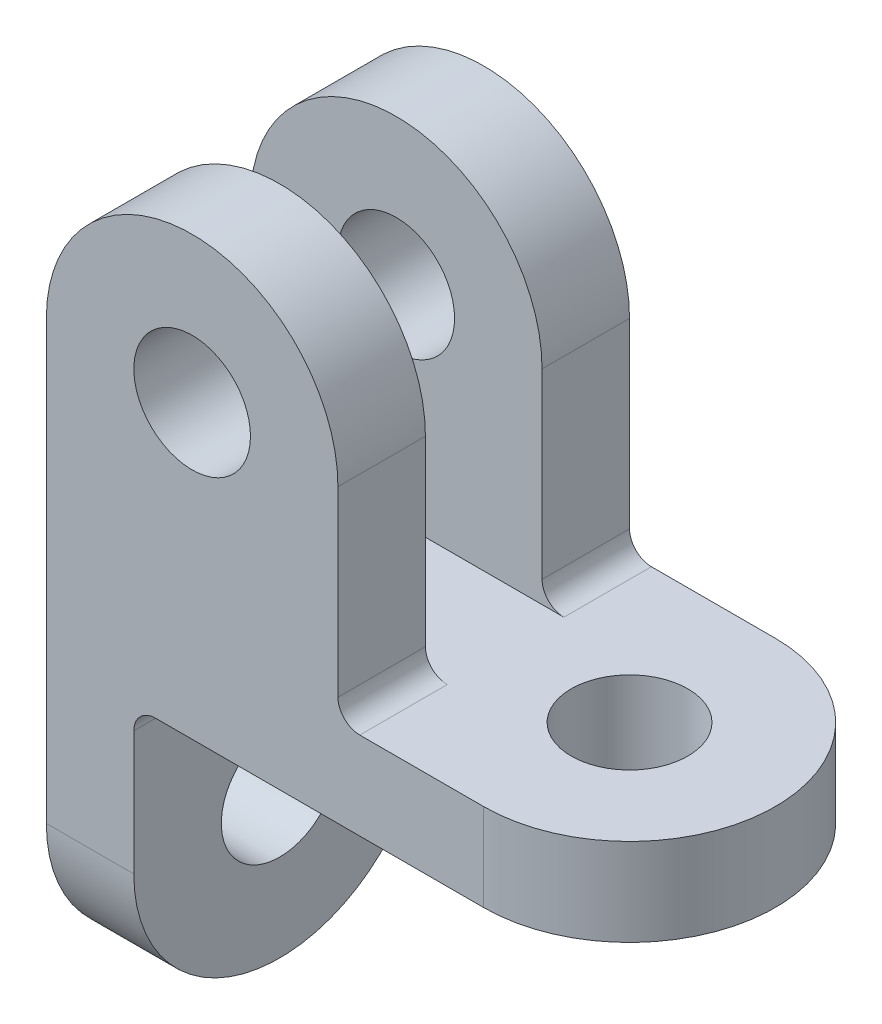
SolidWorks part; units mm, degrees
ref_plane "Front Plane" through (0, 0, 0) normal (0, 0, 1) x (1, 0, 0)
ref_plane "Top Plane" through (0, 0, 0) normal (0, 1, 0) x (1, 0, 0)
ref_plane "Right Plane" through (0, 0, 0) normal (1, 0, 0) x (0, 0, -1)
sketch "Sketch1" plane through (0, 0, 0) normal (0, 0, 1) x (1, 0, 0)
  line L0 (-46.5231, -20) -> (-34.5231, -20)
  line L1 (-34.5231, -20) -> (-34.5231, 0)
  line L2 (-34.5231, 0) -> (13.4769, 0)
  line L3 (13.4769, 0) -> (13.4769, 12)
  line L4 (-6.5231, 40) -> (-46.5231, 40)
  line L5 (-46.5231, 40) -> (-46.5231, -20)
  line L6 (13.4769, 12) -> (-6.5231, 12)
  line L7 (-6.5231, 12) -> (-6.5231, 40)
  dimension "D1" = 12
  dimension "D2" = 60
  dimension "D3" = 12
  dimension "D4" = 40
extrude "Boss-Extrude1" add sketch "Sketch1" along normal blind 40
sketch "Sketch3" plane through (-34.5231, 0, 0) normal (1, 0, 0) x (0, 0, -1)
  line L0 (-40, -20) -> (0, -20) construction
  line L1 (-40, -20) -> (0, -20)
  arc A0 (-40, -20) -> (0, -20) centre (-20, -20) ccw
extrude "Boss-Extrude2" add sketch "Sketch3" against normal up to vertex (12 mm away)
sketch "Sketch4" plane through (-34.5231, 0, 0) normal (1, 0, 0) x (0, 0, -1)
  circle A0 centre (-20, -20) radius 8
  dimension "D1" = 16
extrude "Cut-Extrude1" cut sketch "Sketch4" against normal up to surface (12 mm away) up to face at (-46.5231, 5, 20)
sketch "Sketch5" plane through (0, 12, 0) normal (0, 1, 0) x (1, 0, 0)
  line L0 (13.4769, -40) -> (13.4769, 0) construction
  line L1 (13.4769, 0) -> (13.4769, -40)
  arc A0 (13.4769, -40) -> (13.4769, 0) centre (13.4769, -20) ccw
extrude "Boss-Extrude3" add sketch "Sketch5" against normal up to vertex (12 mm away)
sketch "Sketch6" plane through (0, 12, 0) normal (0, 1, 0) x (1, 0, 0)
  circle A0 centre (13.4769, -20) radius 8
  dimension "D1" = 16
extrude "Cut-Extrude2" cut sketch "Sketch6" against normal up to vertex (12 mm away)
sketch "Sketch8" plane through (0, 0, 40) normal (0, 0, 1) x (1, 0, 0)
  line L0 (-6.5231, 40) -> (-46.5231, 40) construction
  line L1 (-46.5231, 40) -> (-6.5231, 40)
  arc A0 (-6.5231, 40) -> (-46.5231, 40) centre (-26.5231, 40) ccw
extrude "Boss-Extrude4" add sketch "Sketch8" against normal up to vertex (40 mm away)
sketch "Sketch9" plane through (0, 0, 40) normal (0, 0, 1) x (1, 0, 0)
  circle A0 centre (-26.5231, 40) radius 8
  dimension "D1" = 16
extrude "Cut-Extrude3" cut sketch "Sketch9" against normal up to vertex (40 mm away)
sketch "Sketch10" plane through (-6.5231, 0, 0) normal (1, 0, 0) x (0, 0, -1)
  line L0 (-20, 12) -> (-20, 64.6481) construction
  line L1 (0, 12) -> (-40, 12) construction
  line L3 (-12, 12) -> (-28, 12)
  line L4 (-12, 12) -> (-12, 64.6481)
  line L5 (-12, 64.6481) -> (-28, 64.6481)
  line L6 (-28, 12) -> (-28, 64.6481)
  line L7 (-12, 12) -> (-28, 64.6481) construction
  line L8 (-12, 64.6481) -> (-28, 12) construction
  point P4 (-20, 38.3241)
extrude "Cut-Extrude4" cut sketch "Sketch10" against normal blind 62
fillet "Fillet1" radius 3 3 edges at (-34.5231, 0, 20) (-6.5231, 12, 6) (-6.5231, 12, 34)
